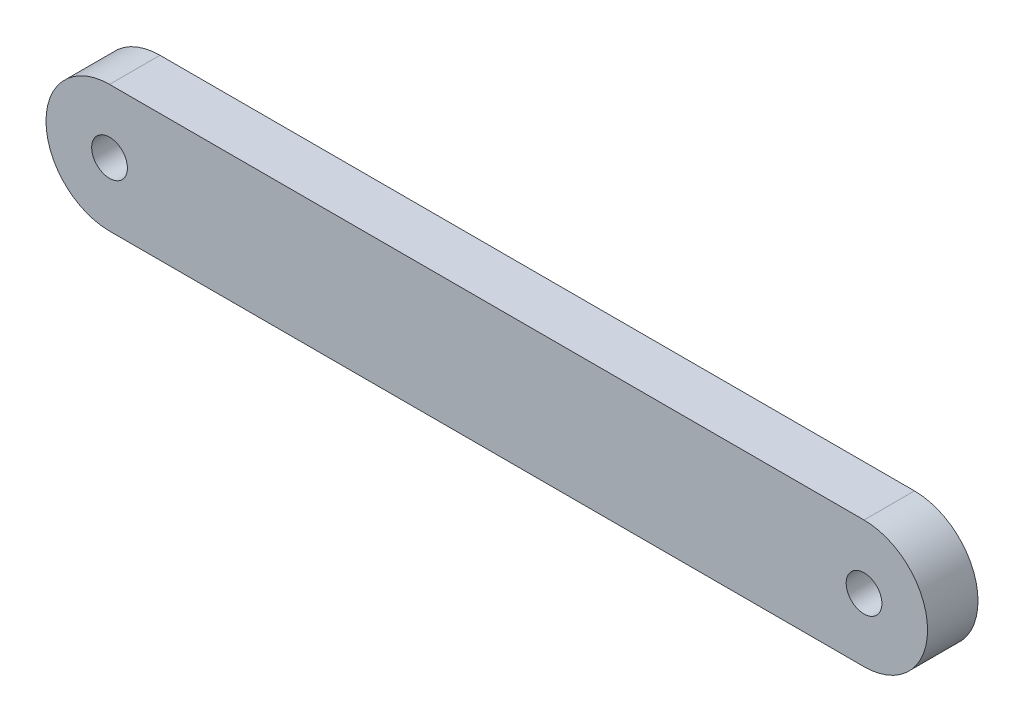
SolidWorks part; units mm, degrees
material "ABS"
ref_plane "Front Plane" through (0, 0, 0) normal (0, 0, 1) x (1, 0, 0)
ref_plane "Top Plane" through (0, 0, 0) normal (0, 1, 0) x (1, 0, 0)
ref_plane "Right Plane" through (0, 0, 0) normal (1, 0, 0) x (0, 0, -1)
sketch "Sketch2" plane through (0, 0, 83.955) normal (0, 0, -1) x (-1, 0, 0)
  line L0 (-47.5, 0) -> (47.5, 0) construction
  line L1 (-47.5, 8) -> (47.5, 8)
  line L2 (-47.5, -8) -> (47.5, -8)
  line L3 (54.5148, -31.5775) -> (-54.5148, -31.5775) construction
  arc A0 (-47.5, 8) -> (-47.5, -8) centre (-47.5, 0) ccw
  arc A1 (47.5, -8) -> (47.5, 8) centre (47.5, 0) ccw
  circle A3 centre (-47.5, 0) radius 2.25
  circle A4 centre (47.5, 0) radius 2.25
  point P2 (0, 0)
  point P11 (0, 0)
  dimension "D2" = 4.5
  dimension "D3" = 8
  dimension "D1" = 95
extrude "Boss-Extrude1" add sketch "Sketch2" along normal blind 6.35
